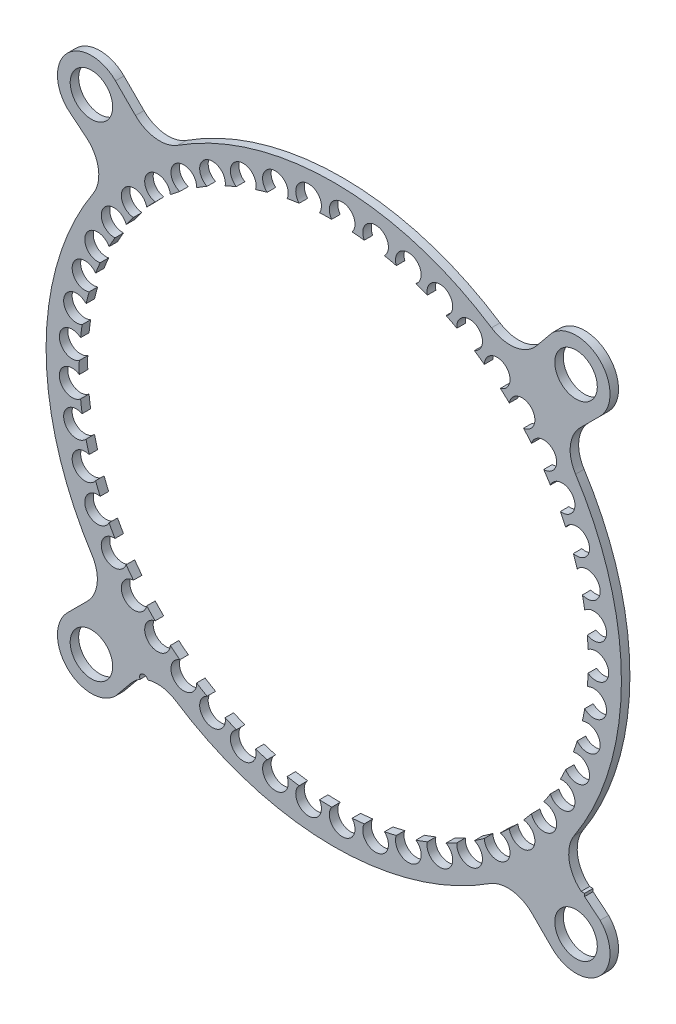
SolidWorks part; units mm, degrees
ref_plane "前视基准面" through (0, 0, 0) normal (0, 0, 1) x (1, 0, 0)
ref_plane "上视基准面" through (0, 0, 0) normal (0, 1, 0) x (1, 0, 0)
ref_plane "右视基准面" through (0, 0, 0) normal (1, 0, 0) x (0, 0, -1)
sketch "草图1" plane through (0, 0, 0) normal (0, 0, 1) x (1, 0, 0)
  line L0 (0, 0.4371) -> (23.55, 0.4371) construction
  line L130 (29.1007, -23.4089) -> (29.5023, -23.4089)
  line L136 (29.5023, -23.4089) -> (29.5023, -23.738)
  line L137 (29.5023, -23.738) -> (31.3282, -25.2342)
  line L139 (28.4997, -28.0626) -> (34.1987, -22.3636) construction
  line L140 (28.4997, -28.0626) -> (24.8719, -31.6905) construction
  line L143 (25.6713, -30.891) -> (23.3201, -28.5398)
  line L144 (-31.3282, -25.2342) -> (-28.9769, -22.8829)
  line L145 (-25.6713, -30.891) -> (-23.8461, -28.6636)
  line L146 (-25.6713, 31.7653) -> (-23.3201, 29.4141)
  line L147 (-31.3282, 26.1085) -> (-29.1007, 24.2832)
  line L148 (31.3282, 26.1085) -> (28.9769, 23.7572)
  line L151 (23.55, 0.4371) -> (23.55, -23.1129) construction
  line L152 (0, 0.4371) -> (23.55, -23.1129) construction
  line L153 (23.55, -23.1129) -> (28.4997, -28.0626) construction
  line L154 (25.6713, 31.7653) -> (23.8461, 29.5379)
  circle A2 centre (15.982, -25.9269) radius 1.51
  circle A3 centre (12.4795, -27.7542) radius 1.51
  circle A4 centre (8.772, -29.1186) radius 1.51
  circle A5 centre (4.9205, -29.9977) radius 1.51
  circle A6 centre (0.9882, -30.377) radius 1.51
  circle A7 centre (-2.9604, -30.2504) radius 1.51
  circle A8 centre (-6.8603, -29.6199) radius 1.51
  circle A9 centre (19.2222, -23.6667) radius 1.51
  circle A10 centre (-10.6476, -28.4958) radius 1.51
  circle A11 centre (-14.2601, -26.8967) radius 1.51
  circle A12 centre (-17.6384, -24.8488) radius 1.51
  circle A13 centre (-20.727, -22.3856) radius 1.51
  circle A14 centre (-23.4754, -19.5477) radius 1.51
  circle A15 centre (-25.8383, -16.3817) radius 1.51
  circle A16 centre (-27.7769, -12.9395) radius 1.51
  circle A17 centre (-29.2594, -9.2776) radius 1.51
  circle A18 centre (-30.2615, -5.4563) radius 1.51
  circle A19 centre (-30.7667, -1.5381) radius 1.51
  circle A20 centre (-30.7667, 2.4124) radius 1.51
  circle A21 centre (-30.2615, 6.3306) radius 1.51
  circle A22 centre (-29.2594, 10.1519) radius 1.51
  circle A23 centre (-27.7769, 13.8138) radius 1.51
  circle A24 centre (-25.8383, 17.256) radius 1.51
  circle A25 centre (-23.4754, 20.422) radius 1.51
  circle A26 centre (-20.727, 23.2599) radius 1.51
  circle A27 centre (-17.6384, 25.7231) radius 1.51
  circle A28 centre (-14.2601, 27.771) radius 1.51
  circle A29 centre (-10.6476, 29.3701) radius 1.51
  circle A30 centre (-6.8603, 30.4942) radius 1.51
  circle A31 centre (-2.9604, 31.1247) radius 1.51
  circle A32 centre (0.9882, 31.2513) radius 1.51
  circle A33 centre (4.9205, 30.872) radius 1.51
  circle A34 centre (8.772, 29.9929) radius 1.51
  circle A35 centre (12.4795, 28.6285) radius 1.51
  circle A36 centre (15.982, 26.8012) radius 1.51
  circle A37 centre (19.2222, 24.541) radius 1.51
  circle A38 centre (22.1467, 21.885) radius 1.51
  circle A39 centre (24.7076, 18.8769) radius 1.51
  circle A40 centre (26.8628, 15.566) radius 1.51
  circle A41 centre (28.5768, 12.0066) radius 1.51
  circle A42 centre (29.8217, 8.2573) radius 1.51
  circle A43 centre (30.5769, 4.3796) radius 1.51
  circle A44 centre (30.83, 0.4371) radius 1.51
  circle A45 centre (30.5769, -3.5053) radius 1.51
  circle A46 centre (29.8217, -7.383) radius 1.51
  circle A47 centre (28.5768, -11.1323) radius 1.51
  circle A48 centre (26.8628, -14.6917) radius 1.51
  circle A49 centre (24.7076, -18.0026) radius 1.51
  circle A50 centre (22.1467, -21.0108) radius 1.51
  circle A172 centre (0, 0.4371) radius 26.5
  arc A184 (-28.9769, -22.8829) -> (-28.4428, -17.8881) centre (-31.8053, -20.0545) ccw
  arc A185 (-28.2914, 18.9953) -> (-29.1007, 24.2832) centre (-31.636, 21.1893) ccw
  circle A187 centre (0, 0.4371) radius 33.835 construction
  circle A189 centre (28.4997, -28.0626) radius 2.5
  circle A192 centre (28.4997, -28.0626) radius 4 construction
  arc A193 (25.6713, -30.891) -> (31.3282, -25.2342) centre (28.4997, -28.0626) ccw
  circle A194 centre (-28.4997, -28.0626) radius 2.5
  arc A195 (-31.3282, -25.2342) -> (-25.6713, -30.891) centre (-28.4997, -28.0626) ccw
  circle A196 centre (-28.4997, 28.9369) radius 2.5
  arc A197 (-25.6713, 31.7653) -> (-31.3282, 26.1085) centre (-28.4997, 28.9369) ccw
  circle A198 centre (28.4997, 28.9369) radius 2.5
  arc A199 (31.3282, 26.1085) -> (25.6713, 31.7653) centre (28.4997, 28.9369) ccw
  arc A200 (-18.5582, -27.8542) -> (18.3252, -28.0057) centre (0, 0.4371) ccw
  arc A201 (-28.4428, -17.8881) -> (-28.2914, 18.9953) centre (0, 0.4371) cw
  arc A202 (-18.3252, 28.88) -> (18.5582, 28.7285) centre (0, 0.4371) cw
  arc A203 (28.4428, 18.7624) -> (28.2914, -18.121) centre (0, 0.4371) cw
  arc A204 (-23.3201, 29.4141) -> (-18.3252, 28.88) centre (-20.4916, 32.2425) ccw
  arc A205 (18.5582, 28.7285) -> (23.8461, 29.5379) centre (20.7521, 32.0731) ccw
  arc A206 (28.4428, 18.7624) -> (28.9769, 23.7572) centre (31.8053, 20.9288) cw
  arc A207 (28.2914, -18.121) -> (29.1007, -23.4089) centre (31.636, -20.315) ccw
  arc A208 (23.3201, -28.5398) -> (18.3252, -28.0057) centre (20.4916, -31.3682) ccw
  arc A209 (-18.5582, -27.8542) -> (-23.8461, -28.6636) centre (-20.7521, -31.1988) ccw
  circle A210 centre (0, 0.4371) radius 30.83 construction
  point P149 (26.1708, -21.0081)
  point P152 (20.9288, -26.1485)
  dimension "D1" = 49
  dimension "D3" = 4
  dimension "D2" = 4
extrude "凸台-拉伸1" add sketch "草图1" along normal blind 1
sketch "草图2" plane through (0, 0, 1) normal (0, 0, 1) x (1, 0, 0)
  circle A0 centre (-22.3345, -27.5251) radius 0.5
  arc A1 (-18.5582, -27.8542) -> (-23.8461, -28.6636) centre (-20.7521, -31.1988) ccw construction
extrude "切除-拉伸1" cut sketch "草图2" against normal blind 10
sketch "草图3" plane through (0, 0, 0) normal (0, 0, -1) x (-1, 0, 0)
  circle A1 centre (0, 0.4371) radius 29.9408
extrude "切除-拉伸2" cut sketch "草图3" against normal blind 10
